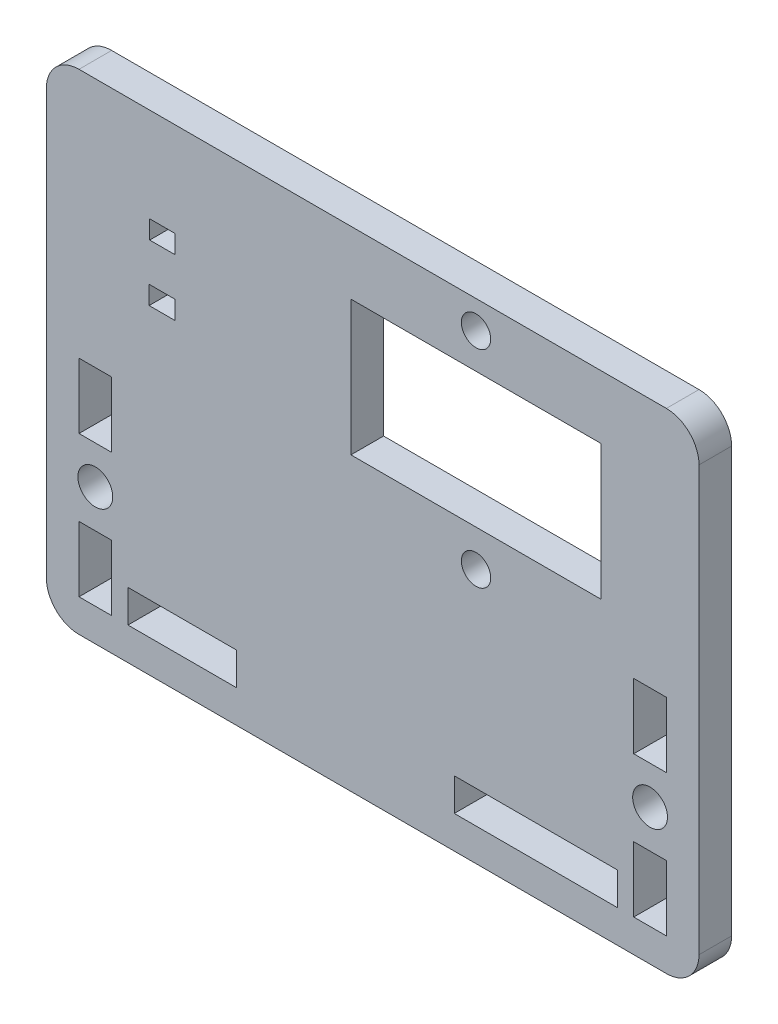
SolidWorks part; units mm, degrees
ref_plane "前视基准面" through (0, 0, 0) normal (0, 0, 1) x (1, 0, 0)
ref_plane "上视基准面" through (0, 0, 0) normal (0, 1, 0) x (1, 0, 0)
ref_plane "右视基准面" through (0, 0, 0) normal (1, 0, 0) x (0, 0, -1)
ref_plane "基准面4" through (0, 0, 0) normal (0, 0, -1) x (-1, 0, 0)
sketch "草图1" plane through (0, 0, 0) normal (0, 0, -1) x (-1, 0, 0)
  line L0 (21.4322, 5.999) -> (21.4322, 2.999)
  line L1 (21.4322, 2.999) -> (11.4322, 2.999)
  line L2 (11.4322, 2.999) -> (11.4322, 5.999)
  line L3 (11.4322, 5.999) -> (21.4322, 5.999)
  line L4 (25.9332, 8.999) -> (25.9332, 2.999)
  line L5 (25.9332, 2.999) -> (22.9332, 2.999)
  line L6 (22.9332, 2.999) -> (22.9332, 8.999)
  line L7 (22.9332, 8.999) -> (25.9332, 8.999)
  line L8 (25.9332, 21.999) -> (25.9332, 15.999)
  line L9 (25.9332, 15.999) -> (22.9332, 15.999)
  line L10 (22.9332, 15.999) -> (22.9332, 21.999)
  line L11 (22.9332, 21.999) -> (25.9332, 21.999)
  line L12 (19.4892, 31.104) -> (19.4892, 29.41)
  line L13 (19.4892, 29.41) -> (17.1082, 29.41)
  line L14 (17.1082, 29.41) -> (17.1082, 31.104)
  line L15 (17.1082, 31.104) -> (19.4892, 31.104)
  line L16 (19.4352, 36.343) -> (19.4352, 34.65)
  line L17 (19.4352, 34.65) -> (17.1082, 34.65)
  line L18 (17.1082, 34.65) -> (17.1082, 36.343)
  line L19 (17.1082, 36.343) -> (19.4352, 36.343)
  line L20 (0.9322, 39.2) -> (0.9322, 26.799)
  line L21 (0.9322, 26.799) -> (-22.0668, 26.799)
  line L22 (-22.0668, 26.799) -> (-22.0668, 39.2)
  line L23 (-22.0668, 39.2) -> (0.9322, 39.2)
  line L24 (-8.5678, 5.999) -> (-8.5678, 2.999)
  line L25 (-8.5678, 2.999) -> (-23.5678, 2.999)
  line L26 (-23.5678, 2.999) -> (-23.5678, 5.999)
  line L27 (-23.5678, 5.999) -> (-8.5678, 5.999)
  line L28 (-25.0668, 8.999) -> (-25.0668, 2.999)
  line L29 (-25.0668, 2.999) -> (-28.0668, 2.999)
  line L30 (-28.0668, 2.999) -> (-28.0668, 8.999)
  line L31 (-28.0668, 8.999) -> (-25.0668, 8.999)
  line L32 (28.9332, 3) -> (28.9332, 41.999)
  line L33 (25.9332, 44.999) -> (-28.0668, 44.999)
  line L34 (-31.0668, 41.999) -> (-31.0668, 3)
  line L35 (-28.0668, 0) -> (25.9332, 0)
  line L36 (-25.0668, 21.999) -> (-25.0668, 15.999)
  line L37 (-25.0668, 15.999) -> (-28.0668, 15.999)
  line L38 (-28.0668, 15.999) -> (-28.0668, 21.999)
  line L39 (-28.0668, 21.999) -> (-25.0668, 21.999)
  arc A0 (25.9332, 0) -> (28.9332, 3) centre (25.9332, 3) ccw
  arc A1 (28.9332, 41.999) -> (25.9332, 44.999) centre (25.9332, 41.999) ccw
  arc A2 (-28.0668, 44.999) -> (-31.0668, 41.999) centre (-28.0668, 41.999) ccw
  arc A3 (-31.0668, 3) -> (-28.0668, 0) centre (-28.0668, 3) ccw
  circle A4 centre (-26.5678, 12.499) radius 1.35
  circle A5 centre (-10.5678, 23.43) radius 1.35
  circle A6 centre (24.4322, 12.499) radius 1.35
  circle A7 centre (-10.5678, 42.429) radius 1.35
  dimension "D1" = 2.7
extrude "凸台-拉伸1" add sketch "草图1" against normal blind 3
sketch "草图2" plane through (0, 0, 3) normal (0, 0, 1) x (1, 0, 0)
  circle A0 centre (-24.4322, 12.499) radius 1.6
  circle A1 centre (26.5678, 12.499) radius 1.6
  dimension "D1" = 3.2
extrude "切除-拉伸1" cut sketch "草图2" against normal through all
